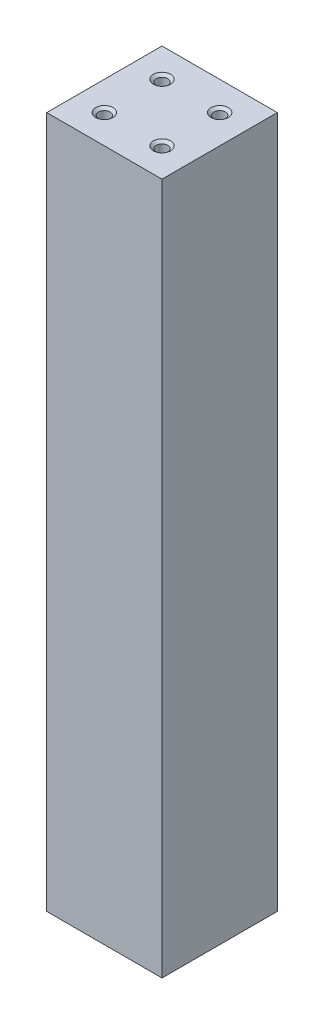
SolidWorks part; units mm, degrees
ref_plane "Front Plane" through (0, 0, 0) normal (0, 0, 1) x (1, 0, 0)
ref_plane "Top Plane" through (0, 0, 0) normal (0, 1, 0) x (1, 0, 0)
ref_plane "Right Plane" through (0, 0, 0) normal (1, 0, 0) x (0, 0, -1)
sketch "Sketch1" plane through (0, 0, 0) normal (0, 1, 0) x (1, 0, 0)
  line L1 (-25.4, -25.4) -> (25.4, -25.4)
  line L2 (-25.4, -25.4) -> (-25.4, 25.4)
  line L3 (-25.4, 25.4) -> (25.4, 25.4)
  line L4 (25.4, -25.4) -> (25.4, 25.4)
  line L5 (0, 25.4) -> (0, -25.4) construction
  line L6 (-25.4, 0) -> (25.4, 0) construction
  point P0 (0, 0)
  dimension "D1" = 50.8
  dimension "D2" = 50.8
extrude "Boss-Extrude1" add sketch "Sketch1" along normal blind 304.8
hole_wizard "1/4-20 Tapped Hole1" positions "Sketch2" profile "Sketch3" tap size "1/4-20" standard "ANSI Inch"
sketch "Sketch2" plane through (0, 304.8, 0) normal (0, 1, 0) x (1, 0, 0)
  point P0 (-12.7, 12.7)
  point P2 (12.7, 12.7)
  point P4 (12.7, -12.7)
  point P6 (-12.7, -12.7)
  point P14 (0, 0)
  point P15 (0, 0)
  point P16 (0, 0)
  point P17 (0, 0)
  point P18 (0, 0)
  point P19 (0, 0)
  dimension "D1" = 12.7
  dimension "D2" = 12.7
  dimension "D3" = 12.7
  dimension "D4" = 12.7
cosmetic thread "Hole Thread1" parameters "D2"=6.35
cosmetic thread "Hole Thread2" parameters "D2"=6.35
cosmetic thread "Hole Thread3" parameters "D2"=6.35
cosmetic thread "Hole Thread4" parameters "D2"=6.35
sketch "Sketch3" plane through (-12.7, 304.8, -12.7) normal (1, 0, 0) x (0, 0, 1)
  line L0 (0, 0) -> (0, 26.9338)
  line L1 (0, 26.9338) -> (2.5527, 25.4)
  line L2 (2.5527, 25.4) -> (2.5527, 1.055)
  line L3 (2.5527, 1.055) -> (3.81, 0)
  line L5 (3.81, 0) -> (0, 0)
  line L6 (-2.5527, 1.055) -> (-3.81, 0) construction
  line L10 (0, 26.9338) -> (-2.5527, 25.4) construction
  line L11 (0, -6.35) -> (0, 107.95) construction
  dimension "Tap Drill Dia." = 5.1054
  dimension "Tap Drill Depth" = 25.4
  dimension "Near C'Sink Dia." = 7.62
  dimension "Near C'Sink Angle" = 100
  dimension "Drill Angle" = 118
ref_plane "Plane1" through (0, 152.4, 0) normal (0, -1, 0) x (-1, 0, 0)
mirror "Mirror1" about plane through (0, 152.4, 0) normal (0, -1, 0) of "1/4-20 Tapped Hole1"
